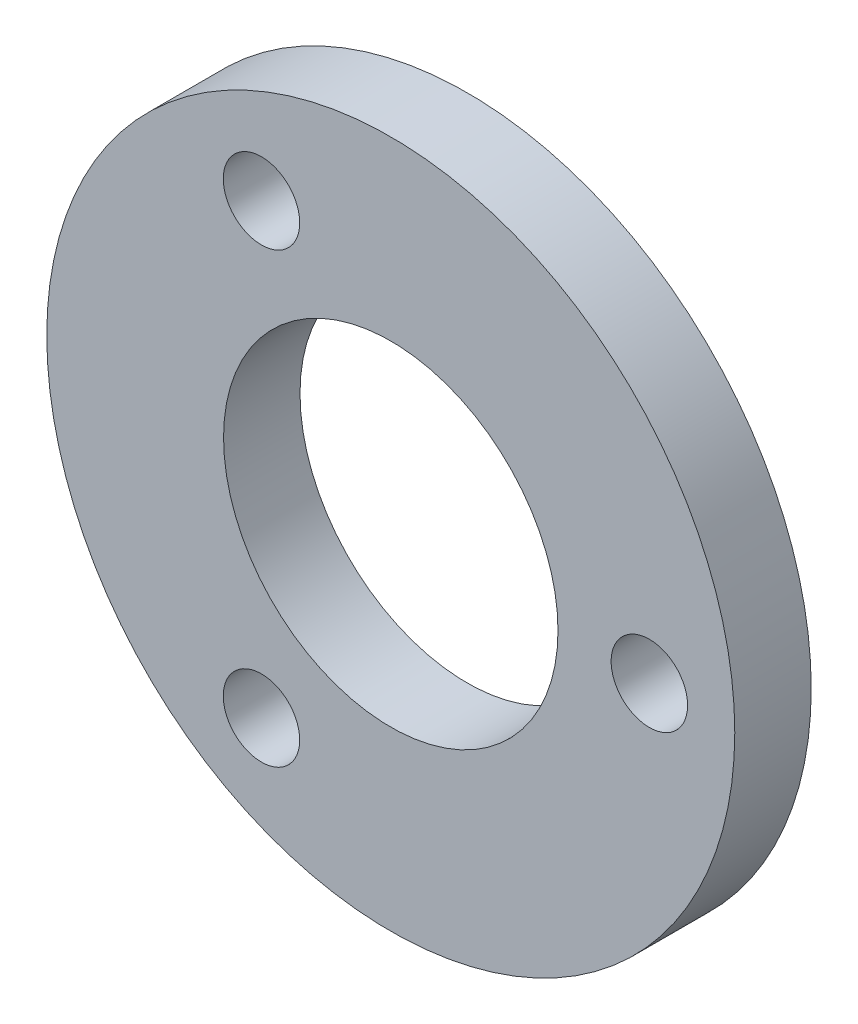
SolidWorks part; units mm, degrees
ref_plane "前视基准面" through (0, 0, 0) normal (0, 0, 1) x (1, 0, 0)
ref_plane "上视基准面" through (0, 0, 0) normal (0, 1, 0) x (1, 0, 0)
ref_plane "右视基准面" through (0, 0, 0) normal (1, 0, 0) x (0, 0, -1)
sketch "草图1" plane through (0, 0, 0) normal (0, 0, 1) x (1, 0, 0)
  circle A0 centre (-0.7367, 0.0914) radius 8.75
  circle A1 centre (-0.7367, 0.0914) radius 13.53 construction
  circle A2 centre (12.7933, 0.0914) radius 2
  circle A5 centre (-0.7367, 0.0914) radius 18
  circle A6 centre (-7.5017, -11.6259) radius 2
  circle A7 centre (-7.5017, 11.8087) radius 2
  dimension "D2" = 3
extrude "凸台-拉伸1" add sketch "草图1" along normal blind 4 contours A5
